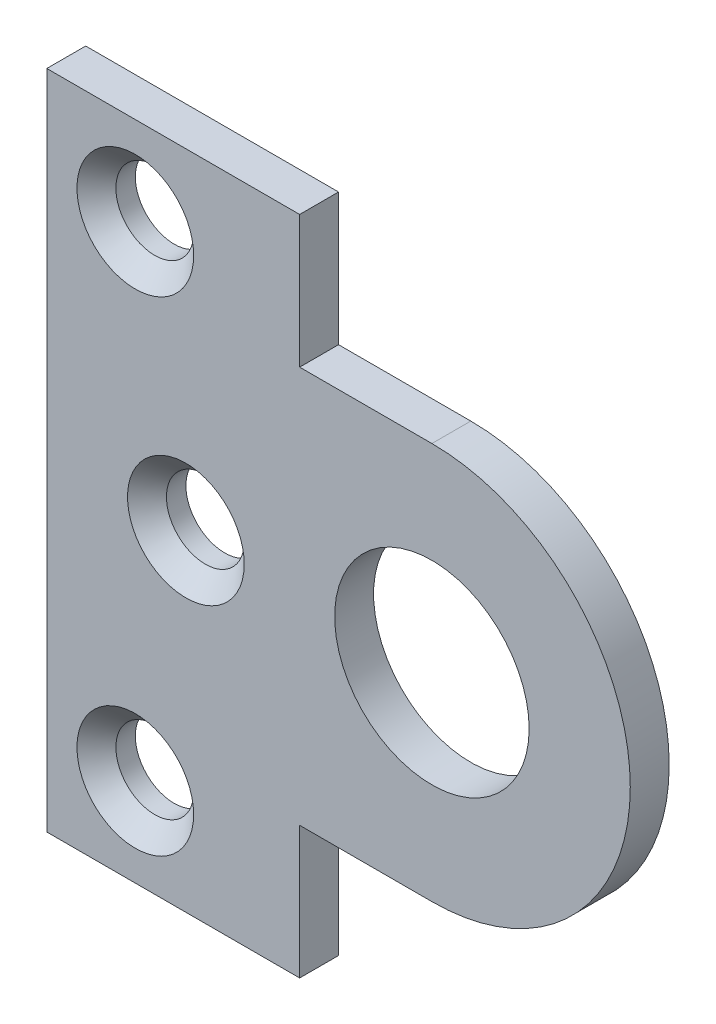
SolidWorks part; units mm, degrees
ref_plane "Front" through (0, 0, 0) normal (0, 0, 1) x (1, 0, 0)
ref_plane "Top" through (0, 0, 0) normal (0, 1, 0) x (1, 0, 0)
ref_plane "Right" through (0, 0, 0) normal (1, 0, 0) x (0, 0, -1)
sketch "Sketch1" plane through (0, 0, 0) normal (0, 0, 1) x (1, 0, 0)
  line L0 (0, 16.1925) -> (-10.795, 16.1925)
  line L1 (-10.795, 16.1925) -> (-10.795, 26.9875)
  line L2 (-10.795, 26.9875) -> (-31.4325, 26.9875)
  line L3 (-31.4325, 26.9875) -> (-31.4325, -26.9875)
  line L4 (-31.4325, -26.9875) -> (-10.795, -26.9875)
  line L5 (-10.795, -26.9875) -> (-10.795, -16.1925)
  line L6 (-10.795, -16.1925) -> (0, -16.1925)
  line L7 (-24.2094, -19.7644) -> (-24.2094, 19.7644) construction
  line L8 (-24.2094, 0) -> (-20.0819, 0) construction
  line L9 (-24.2094, 19.7644) -> (-31.4325, 19.7644) construction
  line L10 (-24.2094, 19.7644) -> (-24.2094, 26.9875) construction
  circle A0 centre (0, 0) radius 7.9375
  circle A1 centre (0, 0) radius 16.1925 construction
  arc A2 (0, -16.1925) -> (0, 16.1925) centre (0, 0) ccw
  circle A3 centre (-24.2094, 19.7644) radius 3.175
  circle A4 centre (-20.0819, 0) radius 3.175
  circle A5 centre (-24.2094, -19.7644) radius 3.175
  point P11 (-31.4325, 0)
  point P13 (16.1925, 0)
  dimension "D1" = 15.875
  dimension "D6" = 6.35
  dimension "D2" = 20.6375
  dimension "D3" = 53.975
  dimension "D4" = 47.625
  dimension "D5" = 32.385
  dimension "D7" = 7.2231
  dimension "D8" = 4.1275
extrude "Boss-Extrude1" add sketch "Sketch1" along normal blind 3.175
chamfer "Chamfer1" distance 1.5875 angle 45 3 edges at (-21.0344, -19.7644, 3.175) (-16.9069, 0, 3.175) (-21.0344, 19.7644, 3.175)
pattern_linear "LPattern1" [suppressed] count 2 spacing 63.5
equation "\"D5@Sketch1\"=\"D3@Sketch1\" * .6"
equation "\"D7@Sketch1\"=\"D2@Sketch1\" * .35"
equation "\"D8@Sketch1\"=\"D2@Sketch1\"/5"
